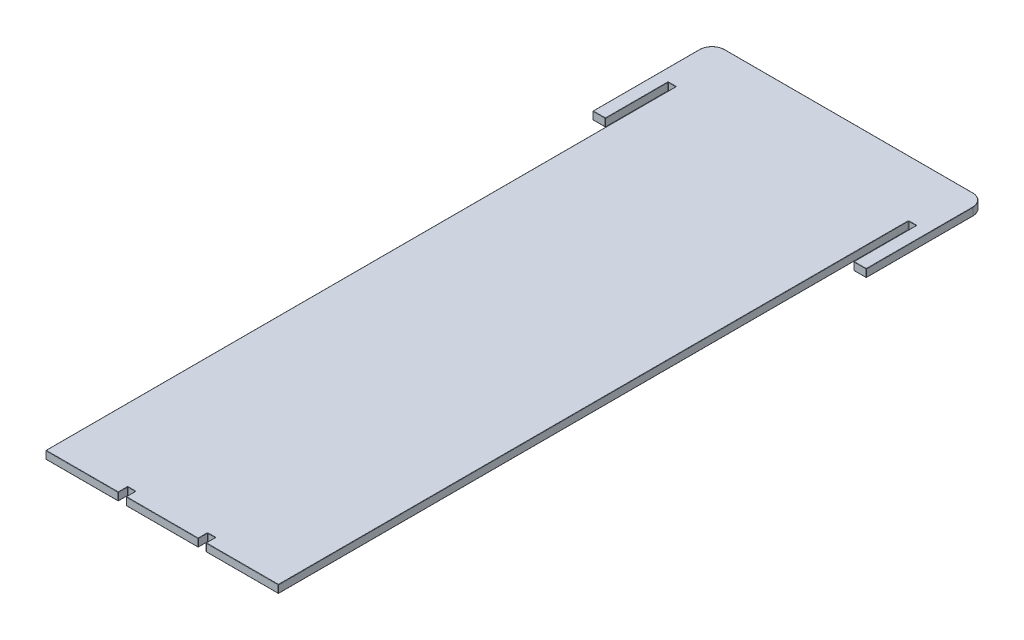
SolidWorks part; units mm, degrees
ref_plane "Plano frontal" through (0, 0, 0) normal (0, 0, 1) x (1, 0, 0)
ref_plane "Plano superior" through (0, 0, 0) normal (0, 1, 0) x (1, 0, 0)
ref_plane "Plano direito" through (0, 0, 0) normal (1, 0, 0) x (0, 0, -1)
sketch "Esboço1" plane through (0, 0, 0) normal (0, 1, 0) x (1, 0, 0)
  line L6 (-192.7976, 36.7977) -> (-118.5976, 36.7977)
  line L7 (-192.7976, 36.7977) -> (-192.7976, -164.2023)
  line L8 (-192.7976, -164.2023) -> (-118.5976, -164.2023)
  line L9 (-118.5976, 36.7977) -> (-118.5976, -164.2023)
  line L10 (-192.7976, 36.7977) -> (-195.2976, 36.7977)
  line L11 (-192.7976, 36.7977) -> (-192.7976, 16.8141)
  line L12 (-192.7976, 16.8141) -> (-195.2976, 16.8141)
  line L19 (-195.2976, 36.7977) -> (-195.2976, 16.8141)
  line L20 (-118.5976, 36.7977) -> (-116.0976, 36.7977)
  line L21 (-118.5976, 36.7977) -> (-118.5976, 16.8141)
  line L22 (-118.5976, 16.8141) -> (-116.0976, 16.8141)
  line L23 (-116.0976, 36.7977) -> (-116.0976, 16.8141)
  line L24 (-199.2976, 16.8141) -> (-112.0976, 16.8141)
  line L25 (-199.2976, 16.8141) -> (-199.2976, 50.8141)
  line L26 (-195.2976, 54.8141) -> (-116.0976, 54.8141)
  line L27 (-112.0976, 16.8141) -> (-112.0976, 50.8141)
  line L28 (-169.6976, -164.2023) -> (-167.1976, -164.2023)
  line L29 (-169.6976, -164.2023) -> (-169.6976, -161.2023)
  line L30 (-169.6976, -161.2023) -> (-167.1976, -161.2023)
  line L31 (-167.1976, -164.2023) -> (-167.1976, -161.2023)
  line L32 (-144.1976, -164.2023) -> (-141.6976, -164.2023)
  line L33 (-144.1976, -164.2023) -> (-144.1976, -161.2023)
  line L34 (-144.1976, -161.2023) -> (-141.6976, -161.2023)
  line L35 (-141.6976, -164.2023) -> (-141.6976, -161.2023)
  arc A3 (-116.0976, 54.8141) -> (-112.0976, 50.8141) centre (-116.0976, 50.8141) cw
  arc A4 (-199.2976, 50.8141) -> (-195.2976, 54.8141) centre (-195.2976, 50.8141) cw
  point P44 (-155.6976, -164.2023)
  dimension "D12" = 4
  dimension "D6" = 74.2
  dimension "D7" = 201
  dimension "D8" = 2.5
  dimension "D9" = 4
  dimension "D10" = 4
  dimension "D13" = 3
  dimension "D14" = 2.5
  dimension "D15" = 11.5
  dimension "D16" = 11.5
extrude "Ressalto-extrusão1" add sketch "Esboço1" along normal blind 2.5 contours L35 L8 L9 L24 L7 L29 L30 L31 L33 L34 | L7 L24 L9 L6 | A4 L25 L24 L19 L10 L6 L20 L23 L27 A3 L26
fillet "Filete1" radius 0.1 62 edges at (-141.6976, 1.25, 164.2023) (-118.5976, 1.25, 164.2023) (-118.5976, 1.25, -36.7977) (-116.0976, 1.25, -36.7977) (-116.0976, 1.25, -16.8141) (-112.0976, 1.25, -16.8141) (-199.2976, 1.25, -16.8141) (-195.2976, 1.25, -16.8141) (-195.2976, 1.25, -36.7977) (-192.7976, 1.25, -36.7977) (-192.7976, 1.25, 164.2023) (-169.6976, 1.25, 164.2023) (-169.6976, 1.25, 161.2023) (-167.1976, 1.25, 161.2023) (-167.1976, 1.25, 164.2023) (-144.1976, 1.25, 164.2023) (-144.1976, 1.25, 161.2023) (-141.6976, 1.25, 161.2023) (-142.9476, 2.5, 161.2023) (-144.1976, 2.5, 162.7023) (-155.6976, 2.5, 164.2023) (-167.1976, 2.5, 162.7023) (-168.4476, 2.5, 161.2023) (-169.6976, 2.5, 162.7023) (-181.2476, 2.5, 164.2023) (-192.7976, 2.5, 63.7023) (-194.0476, 2.5, -36.7977) (-195.2976, 2.5, -26.8059) (-197.2976, 2.5, -16.8141) (-199.2976, 2.5, -33.8141) (-198.1261, 2.5, -53.6425) (-155.6976, 2.5, -54.8141) (-113.2692, 2.5, -53.6425) (-112.0976, 2.5, -33.8141) (-114.0976, 2.5, -16.8141) (-116.0976, 2.5, -26.8059) (-117.3476, 2.5, -36.7977) (-118.5976, 2.5, 63.7023) (-130.1476, 2.5, 164.2023) (-141.6976, 2.5, 162.7023) (-130.1476, 0, 164.2023) (-118.5976, 0, 63.7023) (-117.3476, 0, -36.7977) (-116.0976, 0, -26.8059) (-114.0976, 0, -16.8141) (-112.0976, 0, -33.8141) (-113.2692, 0, -53.6425) (-155.6976, 0, -54.8141) (-198.1261, 0, -53.6425) (-199.2976, 0, -33.8141) (-197.2976, 0, -16.8141) (-195.2976, 0, -26.8059) (-194.0476, 0, -36.7977) (-192.7976, 0, 63.7023) (-181.2476, 0, 164.2023) (-169.6976, 0, 162.7023) (-168.4476, 0, 161.2023) (-167.1976, 0, 162.7023) (-155.6976, 0, 164.2023) (-144.1976, 0, 162.7023) (-142.9476, 0, 161.2023) (-141.6976, 0, 162.7023)
